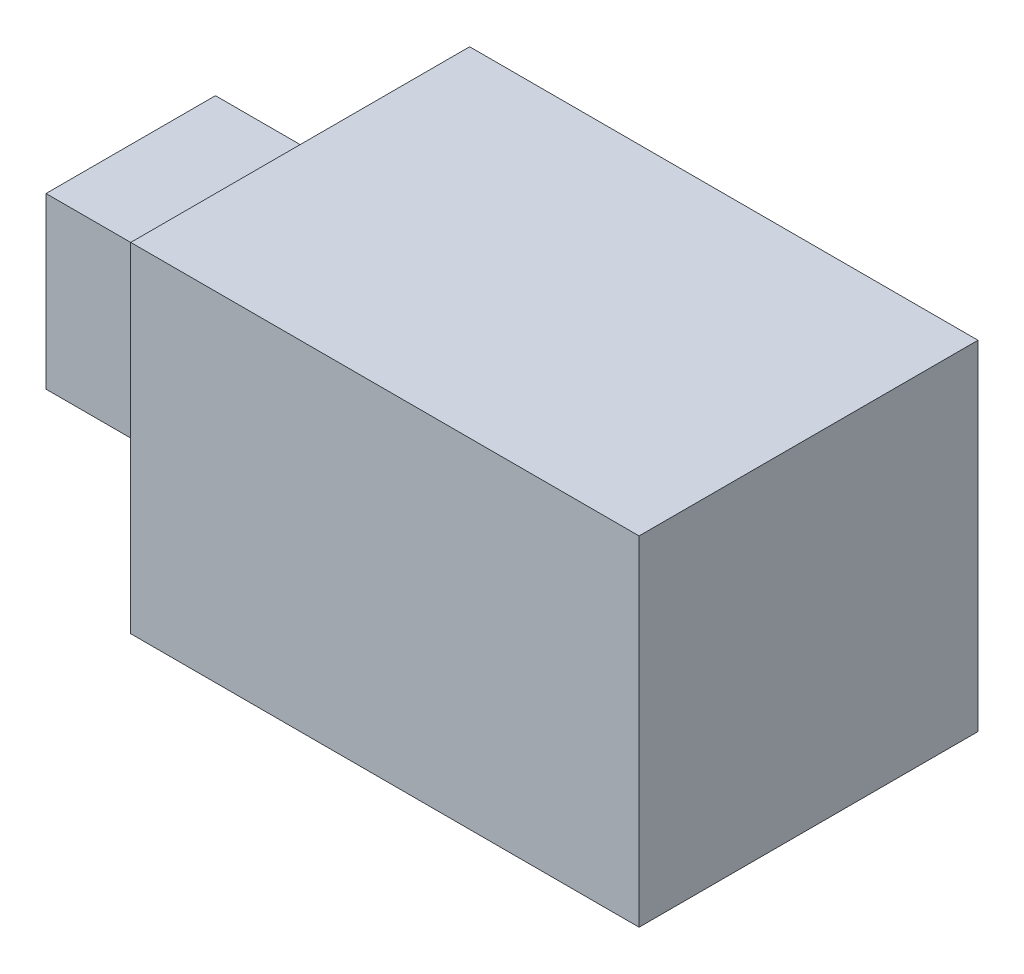
SolidWorks part; units mm, degrees
ref_plane "Front Plane" through (0, 0, 0) normal (0, 0, 1) x (1, 0, 0)
ref_plane "Top Plane" through (0, 0, 0) normal (0, 1, 0) x (1, 0, 0)
ref_plane "Right Plane" through (0, 0, 0) normal (1, 0, 0) x (0, 0, -1)
sketch "Sketch2" plane through (0, 0, 0) normal (1, 0, 0) x (0, 0, -1)
  line L1 (-6.35, 6.35) -> (6.35, 6.35)
  line L2 (-6.35, 6.35) -> (-6.35, -6.35)
  line L3 (-6.35, -6.35) -> (6.35, -6.35)
  line L4 (6.35, 6.35) -> (6.35, -6.35)
  line L5 (-6.35, 6.35) -> (6.35, -6.35) construction
  line L6 (-6.35, -6.35) -> (6.35, 6.35) construction
  point P0 (0, 0)
  dimension "D1" = 12.7
  dimension "D2" = 12.7
extrude "Boss-Extrude1" add sketch "Sketch2" along normal blind 12.7
sketch "Sketch3" plane through (12.7, 0, 0) normal (1, 0, 0) x (0, 0, -1)
  line L1 (-12.7, 12.7) -> (12.7, 12.7)
  line L2 (-12.7, 12.7) -> (-12.7, -12.7)
  line L3 (-12.7, -12.7) -> (12.7, -12.7)
  line L4 (12.7, 12.7) -> (12.7, -12.7)
  line L5 (-12.7, 12.7) -> (12.7, -12.7) construction
  line L6 (-12.7, -12.7) -> (12.7, 12.7) construction
  point P0 (0, 0)
  dimension "D1" = 25.4
  dimension "D2" = 25.4
extrude "Boss-Extrude2" add sketch "Sketch3" along normal blind 38.1
